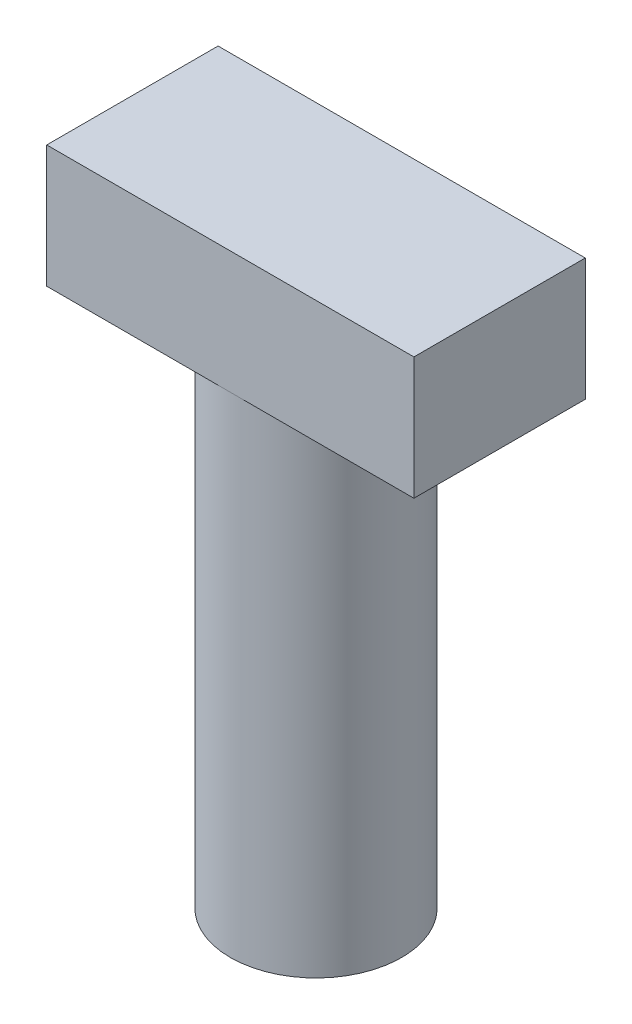
SolidWorks part; units mm, degrees
ref_plane "Front Plane" through (0, 0, 0) normal (0, 0, 1) x (1, 0, 0)
ref_plane "Top Plane" through (0, 0, 0) normal (0, 1, 0) x (1, 0, 0)
ref_plane "Right Plane" through (0, 0, 0) normal (1, 0, 0) x (0, 0, -1)
sketch "Sketch2" plane through (0, 0, 0) normal (0, 1, 0) x (1, 0, 0)
  circle A0 centre (0, 0) radius 7
  dimension "D1" = 14
extrude "Boss-Extrude1" add sketch "Sketch2" along normal blind 40
sketch "Sketch3" plane through (0, 40, 0) normal (0, 1, 0) x (1, 0, 0)
  line L1 (-15, -7) -> (15, -7)
  line L2 (-15, -7) -> (-15, 7)
  line L3 (-15, 7) -> (15, 7)
  line L4 (15, -7) -> (15, 7)
  line L5 (-15, -7) -> (15, 7) construction
  line L6 (-15, 7) -> (15, -7) construction
  point P0 (0, 0)
  point P6 (0, 0)
  point P7 (0, 0)
  dimension "D1" = 14
  dimension "D2" = 30
extrude "Boss-Extrude2" add sketch "Sketch3" along normal blind 10
